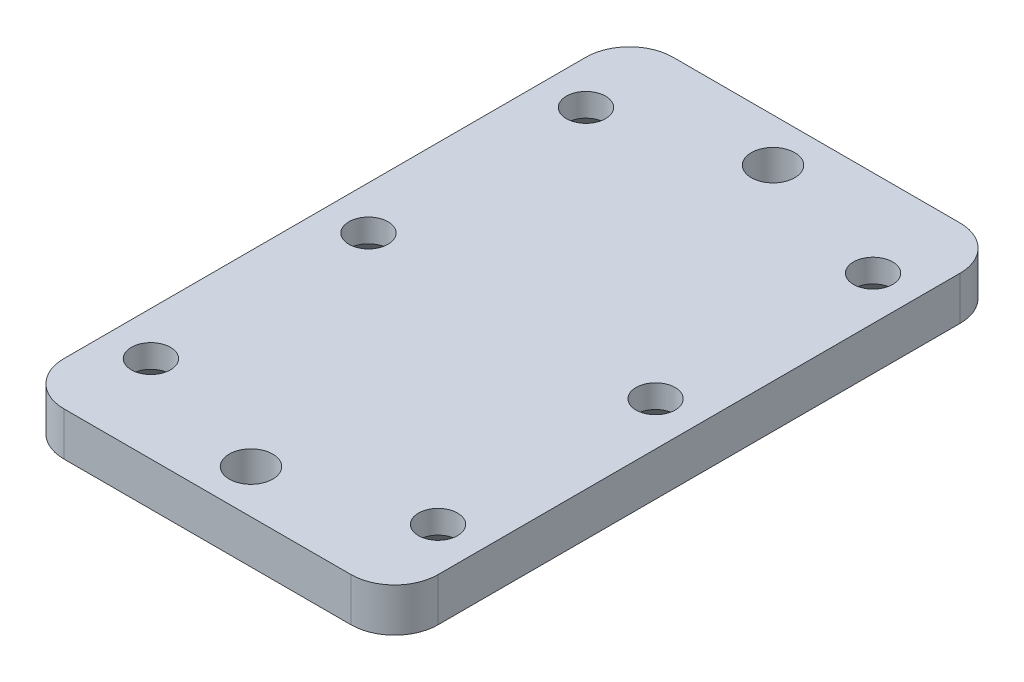
SolidWorks part; units mm, degrees
material "Ti-6Al-2Sn-2Zr-2Mo-2Cr-0.25Si (SS)"
ref_plane "Спереди" through (0, 0, 0) normal (0, 0, 1) x (1, 0, 0)
ref_plane "Сверху" through (0, 0, 0) normal (0, 1, 0) x (1, 0, 0)
ref_plane "Справа" through (0, 0, 0) normal (1, 0, 0) x (0, 0, -1)
sketch "Эскиз2" plane through (0, 0, 0) normal (0, 1, 0) x (1, 0, 0)
  line L0 (0, 37.2124) -> (0, -41.1628) construction
  line L1 (-16.5, -35) -> (16.5, -35)
  line L2 (-21.5, -30) -> (-21.5, 30)
  line L3 (-16.5, 35) -> (16.5, 35)
  line L4 (21.5, -30) -> (21.5, 30)
  line L5 (-21.5, -35) -> (21.5, 35) construction
  line L6 (-21.5, 35) -> (21.5, -35) construction
  line L7 (-26.1502, 0) -> (29.2655, 0) construction
  line L8 (-16.5, 38.5347) -> (-16.5, -56.6696) construction
  line L9 (16.5, 35.6498) -> (16.5, -48.9763) construction
  circle A0 centre (-16.5, -25) radius 2.2
  circle A2 centre (-16.5, 0) radius 2.2
  circle A4 centre (-16.5, 25) radius 2.2
  circle A6 centre (16.5, 0) radius 2.2
  circle A8 centre (16.5, 25) radius 2.2
  circle A9 centre (16.5, -25) radius 2.2
  arc A10 (-16.5, -35) -> (-21.5, -30) centre (-16.5, -30) cw
  arc A11 (16.5, -35) -> (21.5, -30) centre (16.5, -30) ccw
  arc A12 (16.5, 35) -> (21.5, 30) centre (16.5, 30) cw
  arc A13 (-21.5, 30) -> (-16.5, 35) centre (-16.5, 30) cw
  point P0 (0, 0)
  dimension "D4" = 4.4
  dimension "D7" = 5
  dimension "D1" = 70
  dimension "D2" = 43
  dimension "D3" = 33
  dimension "D6" = 25
extrude "Бобышка-Вытянуть1" add sketch "Эскиз2" along normal blind 5
sketch "Эскиз3" plane through (0, 5, 0) normal (0, 1, 0) x (1, 0, 0)
  line L0 (0, 47.1863) -> (0, -49.4094) construction
  line L1 (0, 70) -> (0, 30) construction
  line L2 (3.1, 70) -> (3.1, 30) construction
  line L3 (-3.1, 70) -> (-3.1, 30) construction
  line L4 (0, -30) -> (0, -130) construction
  line L5 (3.1, -30) -> (3.1, -130) construction
  line L6 (-3.1, -30) -> (-3.1, -130) construction
  line L7 (0, 30) -> (41.201, 30) construction
  line L8 (0, -30) -> (53.2431, -30) construction
  line L9 (0, 0) -> (46.4787, 0) construction
  arc A0 (3.1, 70) -> (-3.1, 70) centre (0, 70) ccw construction
  arc A1 (-3.1, 30) -> (3.1, 30) centre (0, 30) ccw construction
  arc A2 (3.1, -30) -> (-3.1, -30) centre (0, -30) ccw construction
  arc A3 (-3.1, -130) -> (3.1, -130) centre (0, -130) ccw construction
  circle A4 centre (0, 30) radius 2
  circle A5 centre (0, -30) radius 2
  point P5 (0, 50)
  point P12 (0, -80)
  dimension "D7" = 4
  dimension "D1" = 6.2
  dimension "D2" = 40
  dimension "D3" = 30
  dimension "D4" = 6.2
  dimension "D6" = 100
extrude "Вырез-Вытянуть1" cut sketch "Эскиз3" against normal blind 50
hole_wizard "Отверстие обработанное метчиком M61" positions "Эскиз4" profile "Эскиз5" tap size "M6" standard "DIN" end condition through all
sketch "Эскиз4" plane through (0, 0, 0) normal (0, 1, 0) x (1, 0, 0)
  point P0 (0, 30)
  point P3 (0, -30)
sketch "Эскиз5" plane through (0, 0, -30) normal (1, 0, 0) x (0, 0, -1)
  line L0 (0, 0) -> (0, 5)
  line L1 (0, 5) -> (2.5, 5)
  line L2 (2.5, 5) -> (2.5, 1)
  line L3 (2.5, 1) -> (3.5, 0)
  line L5 (3.5, 0) -> (0, 0)
  line L6 (-2.5, 1) -> (-3.5, 0) construction
  line L11 (0, -6.35) -> (0, 107.95) construction
  dimension "Диаметр проходного сверла" = 5
  dimension "Глубина проходного сверла" = 5
  dimension "Диаметр передней зенковки" = 7
  dimension "Угол передней зенковки" = 90
cosmetic thread "Отверстие резьбы3" parameters "D2"=6
cosmetic thread "Отверстие резьбы4" parameters "D2"=6
sketch "Эскиз8" plane through (0, 0, 0) normal (0, 1, 0) x (1, 0, 0)
  point P0 (16.5, 25)
  point P3 (16.5, 0)
  point P6 (16.5, -25)
  point P9 (-16.5, -25)
  point P12 (-16.5, 0)
  point P15 (-16.5, 25)
hole_wizard "Зенковка для винта с потайной головкой и внутренним шестигранником M41" positions "Эскиз8" profile "Эскиз7" countersink size "M4" standard "DIN" end condition through all
sketch "Эскиз7" plane through (16.5, 0, -25) normal (1, 0, 0) x (0, 0, -1)
  line L0 (0, 0) -> (0, 5)
  line L1 (0, 5) -> (2.25, 5)
  line L2 (2.25, 5) -> (2.25, 2.34)
  line L3 (2.25, 2.34) -> (4.59, 0)
  line L5 (4.59, 0) -> (0, 0)
  line L6 (-2.25, 2.34) -> (-4.59, 0) construction
  line L11 (0, -6.35) -> (0, 107.95) construction
  dimension "Диаметр сквозного отверстия" = 4.5
  dimension "Глубина сквозного отверстия" = 5
  dimension "Диаметр передней зенковки" = 9.18
  dimension "Угол передней зенковки" = 90
